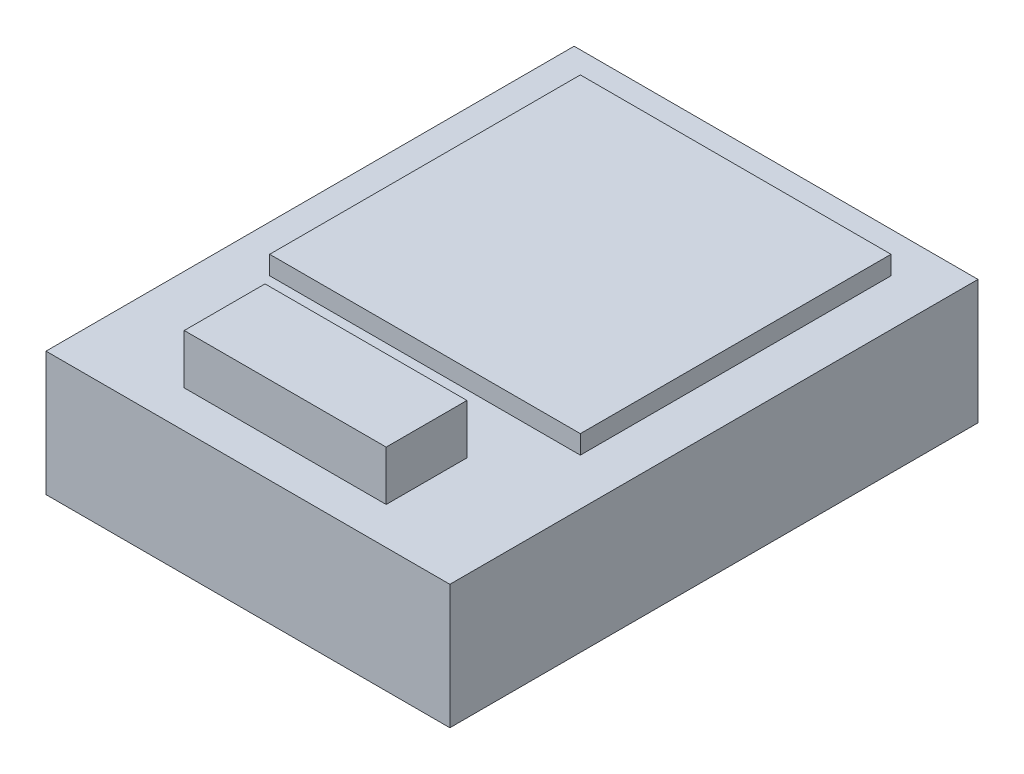
SolidWorks part; units mm, degrees
ref_plane "Front Plane" through (0, 0, 0) normal (0, 0, 1) x (1, 0, 0)
ref_plane "Top Plane" through (0, 0, 0) normal (0, 1, 0) x (1, 0, 0)
ref_plane "Right Plane" through (0, 0, 0) normal (1, 0, 0) x (0, 0, -1)
sketch "Sketch1" plane through (0, 0, 0) normal (0, 1, 0) x (1, 0, 0)
  line L1 (-0.4189, 0.8678) -> (0.8811, 0.8678)
  line L2 (-0.4189, 0.8678) -> (-0.4189, -0.8322)
  line L3 (-0.4189, -0.8322) -> (0.8811, -0.8322)
  line L4 (0.8811, 0.8678) -> (0.8811, -0.8322)
  dimension "D1" = 1.3
  dimension "D2" = 1.7
extrude "Boss-Extrude1" add sketch "Sketch1" along normal blind 0.5
sketch "Sketch2" plane through (0, 0.5, 0) normal (0, 1, 0) x (1, 0, 0)
  line L0 (-0.4189, 0.8678) -> (-0.4189, -0.8322) construction
  line L1 (-0.2689, 0.7378) -> (0.7311, 0.7378)
  line L2 (-0.2689, 0.7378) -> (-0.2689, -0.2622)
  line L3 (-0.2689, -0.2622) -> (0.7311, -0.2622)
  line L4 (0.7311, 0.7378) -> (0.7311, -0.2622)
  line L5 (0.8811, 0.8678) -> (-0.4189, 0.8678) construction
  dimension "D1" = 1
  dimension "D2" = 1
  dimension "D3" = 0.15
  dimension "D4" = 0.13
extrude "Boss-Extrude2" add sketch "Sketch2" along normal blind 0.06
sketch "Sketch3" plane through (0, 0.5, 0) normal (0, 1, 0) x (1, 0, 0)
  line L0 (-0.4189, 0.8678) -> (-0.4189, -0.8322) construction
  line L1 (-0.0939, -0.4522) -> (0.5561, -0.4522)
  line L2 (-0.0939, -0.4522) -> (-0.0939, -0.7122)
  line L3 (-0.0939, -0.7122) -> (0.5561, -0.7122)
  line L4 (0.5561, -0.4522) -> (0.5561, -0.7122)
  line L5 (0.8811, -0.8322) -> (0.8811, 0.8678) construction
  line L6 (-0.4189, -0.8322) -> (0.8811, -0.8322) construction
  dimension "D1" = 0.325
  dimension "D2" = 0.325
  dimension "D3" = 0.12
  dimension "D4" = 0.26
extrude "Boss-Extrude3" add sketch "Sketch3" along normal blind 0.16
sketch "Sketch4" plane through (0, 0, 0) normal (0, -1, 0) x (1, 0, 0)
  line L0 (-0.4189, -0.8678) -> (-0.4189, 0.8322) construction
  line L1 (-0.8987, 1.2077) -> (1.8075, 1.2077)
  line L2 (-0.8987, 1.2077) -> (-0.8987, -1.3416)
  line L3 (-0.8987, -1.3416) -> (1.8075, -1.3416)
  line L4 (1.8075, 1.2077) -> (1.8075, -1.3416)
  line L5 (-0.2939, 0.7322) -> (0.1061, 0.7322)
  line L6 (-0.2939, 0.7322) -> (-0.2939, -0.7678)
  line L7 (-0.2939, -0.7678) -> (0.1061, -0.7678)
  line L8 (0.1061, 0.7322) -> (0.1061, -0.7678)
  line L9 (0.3561, 0.7322) -> (0.7561, 0.7322)
  line L10 (0.3561, 0.7322) -> (0.3561, -0.7678)
  line L11 (0.3561, -0.7678) -> (0.7561, -0.7678)
  line L12 (0.7561, 0.7322) -> (0.7561, -0.7678)
  line L13 (-0.4189, 0.8322) -> (0.8811, 0.8322) construction
  dimension "D1" = 0.4
  dimension "D2" = 0.4
  dimension "D3" = 1.05
  dimension "D4" = 1.5
  dimension "D5" = 1.5
  dimension "D6" = 0.125
  dimension "D7" = 0.1
  dimension "D8" = 0.1
extrude "Cut-Extrude1" cut sketch "Sketch4" against normal blind 0.1
